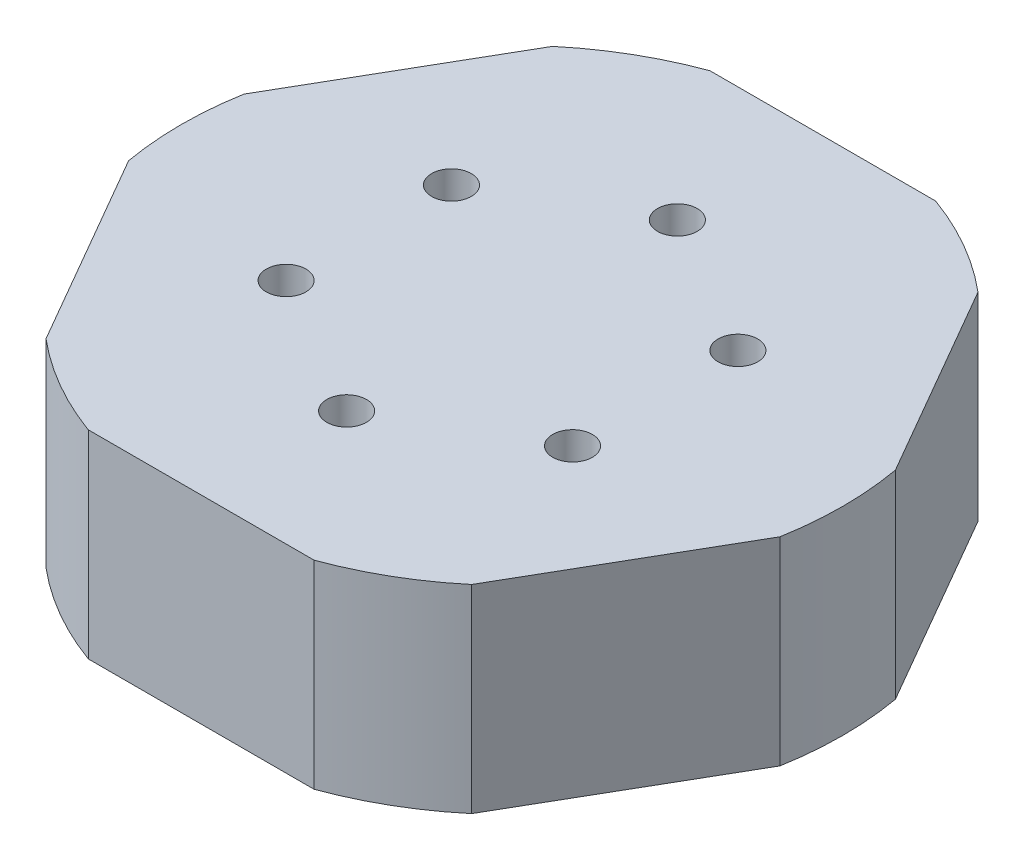
SolidWorks part; units mm, degrees
ref_plane "Front Plane" through (0, 0, 0) normal (0, 0, 1) x (1, 0, 0)
ref_plane "Top Plane" through (0, 0, 0) normal (0, 1, 0) x (1, 0, 0)
ref_plane "Right Plane" through (0, 0, 0) normal (1, 0, 0) x (0, 0, -1)
sketch "Sketch2" plane through (0, 0, 0) normal (0, 1, 0) x (1, 0, 0)
  circle A0 centre (0, 0) radius 40
  dimension "D1" = 80
extrude "Boss-Extrude1" add sketch "Sketch2" along normal blind 10
sketch "Sketch3" plane through (0, 0, 0) normal (0, -1, 0) x (1, 0, 0)
  circle A0 centre (0, 0) radius 40
  circle A1 centre (0, 0) radius 40 construction
extrude "Extrude-Thin1" add sketch "Sketch3" along normal blind 20 and the other way blind 10 thin
sketch "Sketch4" plane through (0, 10, 0) normal (0, 1, 0) x (1, 0, 0)
  line L0 (0, -50) -> (0, -47) construction
  line L1 (54.2709, 0) -> (27.1355, 47)
  line L2 (27.1355, 47) -> (-27.1355, 47)
  line L3 (-27.1355, 47) -> (-54.2709, 0)
  line L4 (-54.2709, 0) -> (-27.1355, -47)
  line L5 (-27.1355, -47) -> (27.1355, -47)
  line L6 (27.1355, -47) -> (54.2709, 0)
  circle A0 centre (0, 0) radius 47 construction
  circle A1 centre (0, 0) radius 50 construction
  dimension "D1" = 3
extrude "Cut-Extrude1" cut sketch "Sketch4" against normal through all flip side to cut
sketch "Sketch5" plane through (0, 10, 0) normal (0, 1, 0) x (1, 0, 0)
  circle A0 centre (0, 0) radius 25 construction
  circle A1 centre (0, 25) radius 3
  circle A2 centre (21.6506, 12.5) radius 3
  circle A3 centre (21.6506, -12.5) radius 3
  circle A4 centre (0, -25) radius 3
  circle A5 centre (-21.6506, -12.5) radius 3
  circle A6 centre (-21.6506, 12.5) radius 3
  point P17 (0, 0)
  dimension "D1" = 50
  dimension "D2" = 6
  dimension "D3" = 6
extrude "Cut-Extrude2" cut sketch "Sketch5" against normal through all
